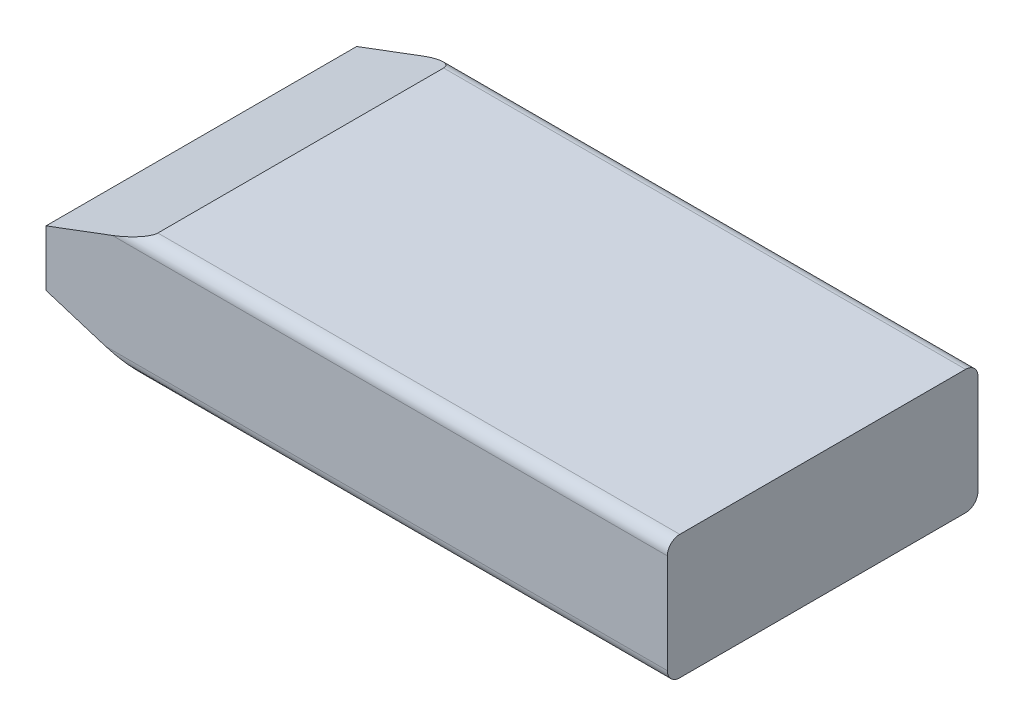
SolidWorks part; units mm, degrees
ref_plane "前视基准面" through (0, 0, 0) normal (0, 0, 1) x (1, 0, 0)
ref_plane "上视基准面" through (0, 0, 0) normal (0, 1, 0) x (1, 0, 0)
ref_plane "右视基准面" through (0, 0, 0) normal (1, 0, 0) x (0, 0, -1)
other "Configuration Table"
sketch "草图1" plane through (0, 0, 0) normal (0, 1, 0) x (1, 0, 0)
  line L1 (-25, -12.5) -> (25, -12.5)
  line L2 (-25, -12.5) -> (-25, 12.5)
  line L3 (-25, 12.5) -> (25, 12.5)
  line L4 (25, -12.5) -> (25, 12.5)
  line L5 (-25, -12.5) -> (25, 12.5) construction
  line L6 (-25, 12.5) -> (25, -12.5) construction
  point P0 (0, 0)
  dimension "D1" = 50
  dimension "D2" = 25
extrude "凸台-拉伸1" add sketch "草图1" along normal blind 10
fillet "圆角1" radius 1 4 edges at (0, 0, 12.5) (0, 10, 12.5) (0, 10, -12.5) (0, 0, -12.5)
sketch "草图2" plane through (0, 0, 12.5) normal (0, 0, 1) x (1, 0, 0)
  line L0 (-25, 7) -> (-17, 10)
  line L1 (-25, 9) -> (-25, 1) construction
  line L2 (-25, 10) -> (25, 10) construction
  line L3 (-17, 10) -> (-17, 12)
  line L4 (-17, 12) -> (-27, 12)
  line L5 (-27, 12) -> (-27, -2)
  line L6 (-27, -2) -> (-17, -2)
  line L7 (-17, -2) -> (-17, 0)
  line L8 (25, 0) -> (-25, 0) construction
  line L9 (-17, 0) -> (-25, 2.5)
  line L10 (-25, 2.5) -> (-25, 7)
  dimension "D1" = 8
  dimension "D2" = 8
  dimension "D3" = 4.5
  dimension "D4" = 2.5
  dimension "D5" = 10
  dimension "D6" = 2
  dimension "D7" = 2
extrude "切除-拉伸1" cut sketch "草图2" against normal blind 28
